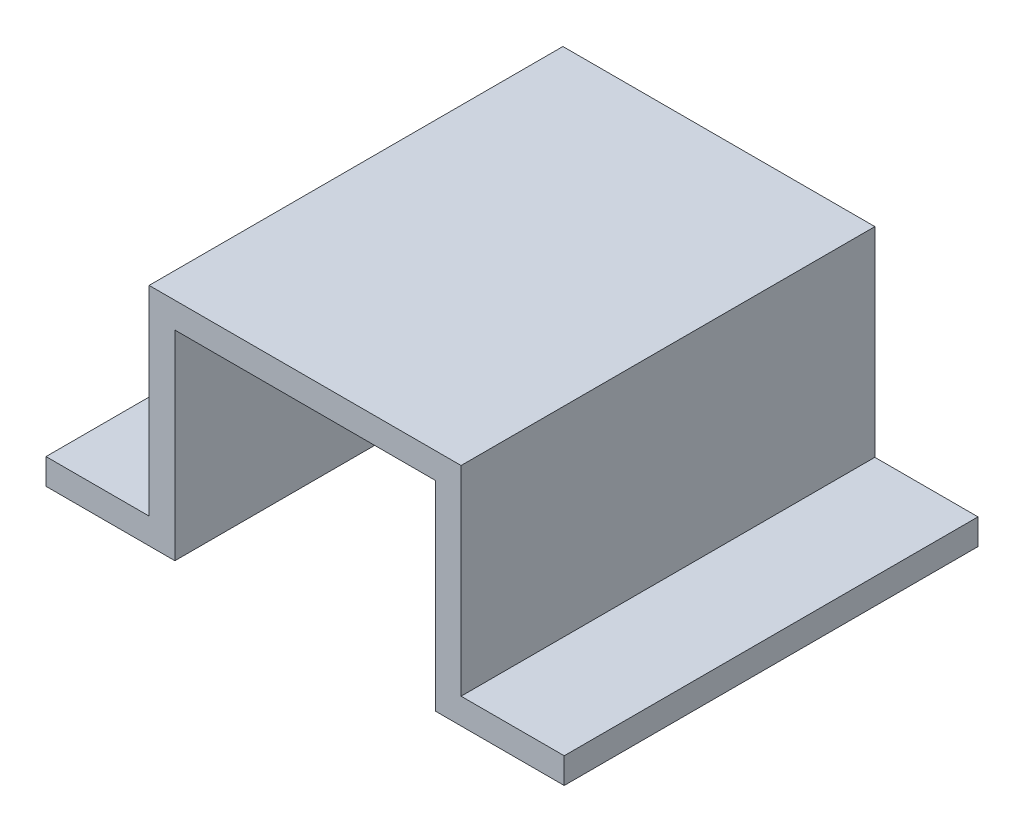
SolidWorks part; units mm, degrees
ref_plane "Front Plane" through (0, 0, 0) normal (0, 0, 1) x (1, 0, 0)
ref_plane "Top Plane" through (0, 0, 0) normal (0, 1, 0) x (1, 0, 0)
ref_plane "Right Plane" through (0, 0, 0) normal (1, 0, 0) x (0, 0, -1)
sketch "Sketch1" plane through (0, 0, 0) normal (0, 0, 1) x (1, 0, 0)
  line L0 (26.177, -18.6609) -> (16.177, -18.6609)
  line L1 (16.177, -18.6609) -> (16.177, -3.1609)
  line L2 (16.177, -3.1609) -> (-4.023, -3.1609)
  line L3 (-4.023, -3.1609) -> (-4.023, -18.6609)
  line L4 (-4.023, -18.6609) -> (-14.023, -18.6609)
  line L5 (-14.023, -18.6609) -> (-14.023, -16.6609)
  line L6 (-14.023, -16.6609) -> (-6.023, -16.6609)
  line L7 (-6.023, -16.6609) -> (-6.023, -1.1609)
  line L8 (-6.023, -1.1609) -> (18.177, -1.1609)
  line L9 (18.177, -1.1609) -> (18.177, -16.6609)
  line L10 (18.177, -16.6609) -> (26.177, -16.6609)
  line L11 (26.177, -16.6609) -> (26.177, -18.6609)
  dimension "D1" = 10
  dimension "D2" = 2
  dimension "D3" = 20.2
  dimension "D4" = 8
  dimension "D5" = 15.5
  dimension "D6" = 2
extrude "Boss-Extrude1" add sketch "Sketch1" against normal blind 32.1
